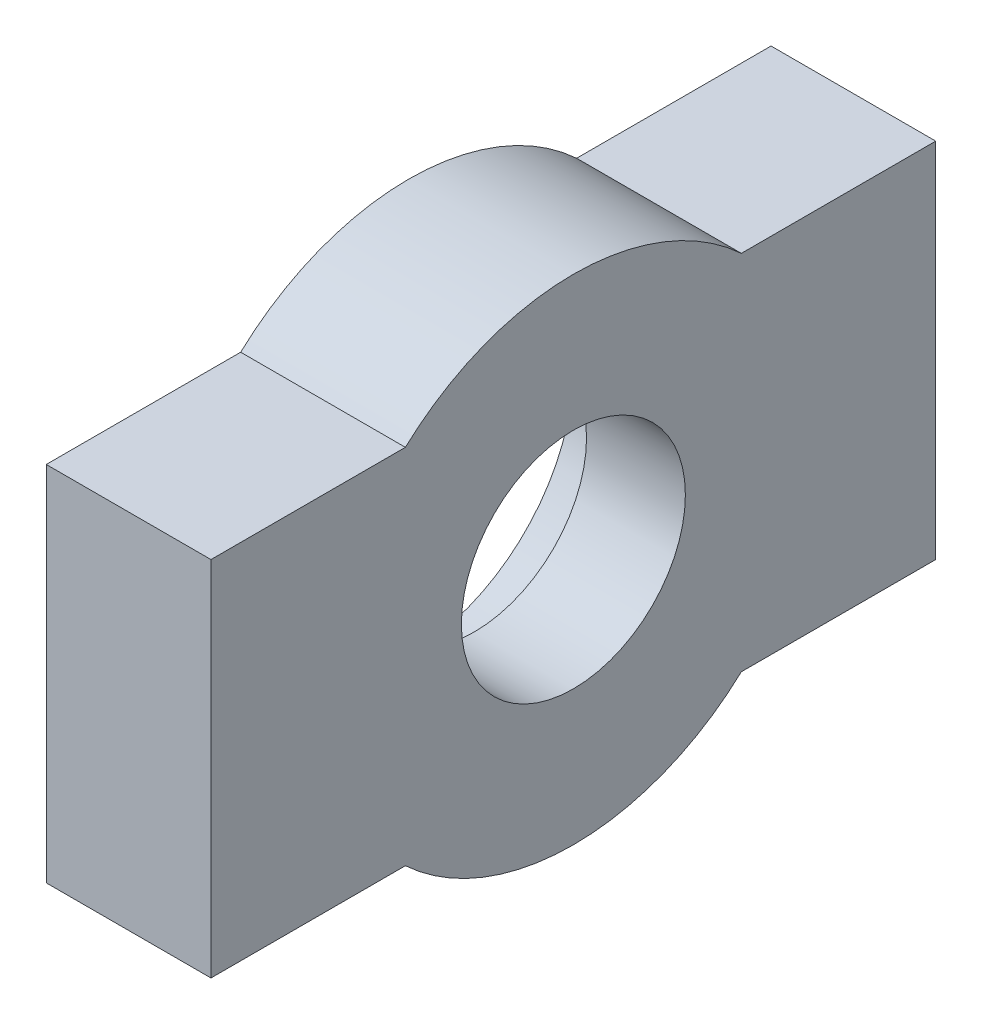
SolidWorks part; units mm, degrees
ref_plane "前视基准面" through (0, 0, 0) normal (0, 0, 1) x (1, 0, 0)
ref_plane "上视基准面" through (0, 0, 0) normal (0, 1, 0) x (1, 0, 0)
ref_plane "右视基准面" through (0, 0, 0) normal (1, 0, 0) x (0, 0, -1)
sketch "草图1" plane through (0, 0, 0) normal (1, 0, 0) x (0, 0, -1)
  circle A0 centre (0, 0) radius 7.5
  dimension "D1" = 15
extrude "凸台-拉伸1" add sketch "草图1" along normal blind 5
sketch "草图2" plane through (0, 0, 0) normal (-1, 0, 0) x (0, 0, 1)
  circle A0 centre (0, 0) radius 5
  dimension "D1" = 10
extrude "切除-拉伸1" cut sketch "草图2" against normal blind 2
sketch "草图3" plane through (2, 0, 0) normal (-1, 0, 0) x (0, 0, 1)
  circle A0 centre (0, 0) radius 3.4
  dimension "D1" = 6.8
extrude "切除-拉伸2" cut sketch "草图3" against normal through all
sketch "草图4" plane through (0, 0, 0) normal (-1, 0, 0) x (0, 0, 1)
  line L1 (5, 5.5) -> (11, 5.5)
  line L2 (5, 5.5) -> (5, -5.5)
  line L3 (5, -5.5) -> (11, -5.5)
  line L4 (11, 5.5) -> (11, -5.5)
  line L5 (-11, 5.5) -> (-5, 5.5)
  line L6 (-11, 5.5) -> (-11, -5.5)
  line L7 (-11, -5.5) -> (-5, -5.5)
  line L8 (-5, 5.5) -> (-5, -5.5)
  circle A0 centre (0, 0) radius 7.5 construction
  dimension "D1" = 6
  dimension "D2" = 11
  dimension "D3" = 5.5
  dimension "D4" = 5
  dimension "D5" = 6
  dimension "D6" = 11
  dimension "D7" = 5.5
  dimension "D8" = 5
extrude "凸台-拉伸2" add sketch "草图4" against normal blind 5
